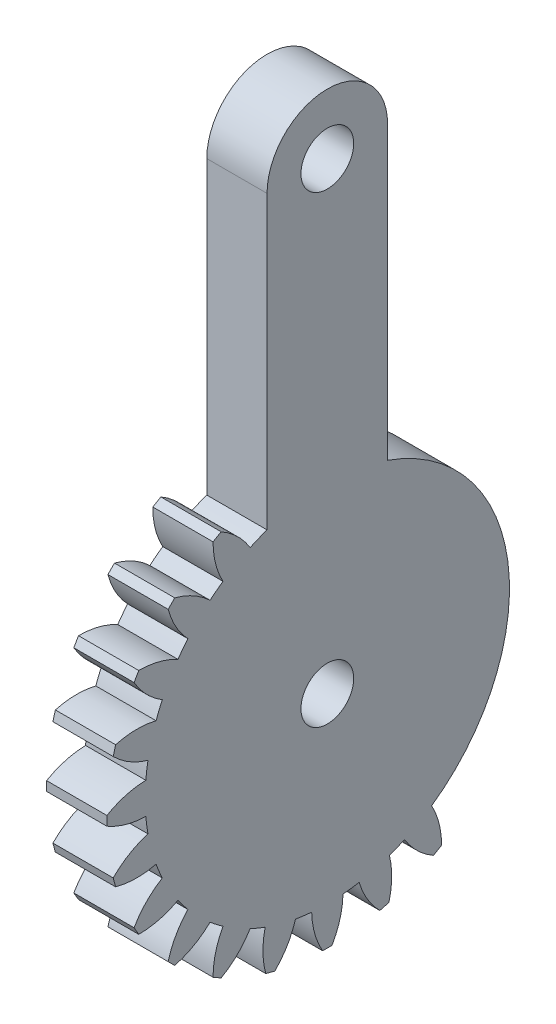
SolidWorks part; units mm, degrees
ref_plane "Front Plane" through (0, 0, 0) normal (1, 0, 0) x (0, 1, 0)
ref_plane "Top Plane" through (0, 0, 0) normal (0, 0, 1) x (0, 1, 0)
ref_plane "Right Plane" through (0, 0, 0) normal (0, 1, 0) x (-1, 0, 0)
sketch "Sketch1" plane through (0, 0, 0) normal (1, 0, 0) x (0, 1, 0)
  line L0 (0, 0) -> (30.75, 0) construction
  line L1 (0, 14.63) -> (0, -14.63) construction
  line L2 (-0.31, 14.63) -> (0.31, 14.63)
  line L3 (3.4871, 14.2117) -> (4.086, 14.0513)
  line L4 (7.0465, 12.825) -> (7.5835, 12.515)
  line L5 (10.1258, 10.5642) -> (10.5642, 10.1258)
  line L6 (12.515, 7.5835) -> (12.825, 7.0465)
  line L10 (12.825, -7.0465) -> (12.515, -7.5835)
  line L11 (10.5642, -10.1258) -> (10.1258, -10.5642)
  line L12 (7.5835, -12.515) -> (7.0465, -12.825)
  line L13 (4.086, -14.0513) -> (3.4871, -14.2117)
  line L14 (0.31, -14.63) -> (-0.31, -14.63)
  line L15 (-3.4871, -14.2117) -> (-4.086, -14.0513)
  line L16 (-7.0465, -12.825) -> (-7.5835, -12.515)
  line L17 (-10.1258, -10.5642) -> (-10.5642, -10.1258)
  line L18 (-12.515, -7.5835) -> (-12.825, -7.0465)
  line L19 (-14.0513, -4.086) -> (-14.2117, -3.4871)
  line L20 (-14.63, -0.31) -> (-14.63, 0.31)
  line L21 (-14.2117, 3.4871) -> (-14.0513, 4.086)
  line L22 (-12.825, 7.0465) -> (-12.515, 7.5835)
  line L23 (-10.5642, 10.1258) -> (-10.1258, 10.5642)
  line L24 (-7.5835, 12.515) -> (-7.0465, 12.825)
  line L25 (-4.086, 14.0513) -> (-3.4871, 14.2117)
  line L26 (30.75, 4) -> (30.75, -4) construction
  line L27 (30.75, 4) -> (11.4091, 4)
  line L28 (30.75, -4) -> (11.4091, -4)
  line L29 (14.0743, 4) -> (14.2117, 3.4871) [skipped]
  line L30 (14.63, 0) -> (14.63, -0.31) [skipped]
  line L31 (14.0743, -4) -> (14.0513, -4.086) [skipped]
  arc A0 (-6.9233, 9.9114) -> (-7.7818, 9.2526) centre (0, 0) ccw
  circle A1 centre (0, 0) radius 1.75
  circle A2 centre (30.75, 0) radius 1.75
  arc A3 (-1.04, 12.0452) -> (-0.31, 14.63) centre (4.3585, 11.9161) cw
  arc A4 (1.04, 12.0452) -> (0.31, 14.63) centre (-4.3585, 11.9161) ccw
  arc A5 (2.113, 11.9039) -> (3.4871, 14.2117) centre (7.294, 10.382) cw
  arc A6 (4.1221, 11.3656) -> (4.086, 14.0513) centre (-1.1258, 12.6381) ccw
  arc A7 (5.1219, 10.9514) -> (7.0465, 12.825) centre (9.7326, 8.1404) cw
  arc A8 (6.9233, 9.9114) -> (7.5835, 12.515) centre (2.1835, 12.4988) ccw
  arc A9 (7.7818, 9.2526) -> (10.1258, 10.5642) centre (11.5078, 5.344) cw
  arc A10 (9.2526, 7.7818) -> (10.5642, 10.1258) centre (5.344, 11.5078) ccw
  arc A11 (9.9114, 6.9233) -> (12.515, 7.5835) centre (12.4988, 2.1835) cw
  arc A12 (10.9514, 5.1219) -> (12.825, 7.0465) centre (8.1404, 9.7326) ccw
  arc A13 (11.4091, 4) -> (10.9514, 5.1219) centre (0, 0) ccw
  arc A19 (10.9514, -5.1219) -> (12.825, -7.0465) centre (8.1404, -9.7326) cw
  arc A20 (9.9114, -6.9233) -> (12.515, -7.5835) centre (12.4988, -2.1835) ccw
  arc A21 (9.2526, -7.7818) -> (10.5642, -10.1258) centre (5.344, -11.5078) cw
  arc A22 (7.7818, -9.2526) -> (10.1258, -10.5642) centre (11.5078, -5.344) ccw
  arc A23 (6.9233, -9.9114) -> (7.5835, -12.515) centre (2.1835, -12.4988) cw
  arc A24 (5.1219, -10.9514) -> (7.0465, -12.825) centre (9.7326, -8.1404) ccw
  arc A25 (4.1221, -11.3656) -> (4.086, -14.0513) centre (-1.1258, -12.6381) cw
  arc A26 (2.113, -11.9039) -> (3.4871, -14.2117) centre (7.294, -10.382) ccw
  arc A27 (1.04, -12.0452) -> (0.31, -14.63) centre (-4.3585, -11.9161) cw
  arc A28 (-1.04, -12.0452) -> (-0.31, -14.63) centre (4.3585, -11.9161) ccw
  arc A29 (-2.113, -11.9039) -> (-3.4871, -14.2117) centre (-7.294, -10.382) cw
  arc A30 (-4.1221, -11.3656) -> (-4.086, -14.0513) centre (1.1258, -12.6381) ccw
  arc A31 (-5.1219, -10.9514) -> (-7.0465, -12.825) centre (-9.7326, -8.1404) cw
  arc A32 (-6.9233, -9.9114) -> (-7.5835, -12.515) centre (-2.1835, -12.4988) ccw
  arc A33 (-7.7818, -9.2526) -> (-10.1258, -10.5642) centre (-11.5078, -5.344) cw
  arc A34 (-9.2526, -7.7818) -> (-10.5642, -10.1258) centre (-5.344, -11.5078) ccw
  arc A35 (-9.9114, -6.9233) -> (-12.515, -7.5835) centre (-12.4988, -2.1835) cw
  arc A36 (-10.9514, -5.1219) -> (-12.825, -7.0465) centre (-8.1404, -9.7326) ccw
  arc A37 (-11.3656, -4.1221) -> (-14.0513, -4.086) centre (-12.6381, 1.1258) cw
  arc A38 (-11.9039, -2.113) -> (-14.2117, -3.4871) centre (-10.382, -7.294) ccw
  arc A39 (-12.0452, -1.04) -> (-14.63, -0.31) centre (-11.9161, 4.3585) cw
  arc A40 (-12.0452, 1.04) -> (-14.63, 0.31) centre (-11.9161, -4.3585) ccw
  arc A41 (-11.9039, 2.113) -> (-14.2117, 3.4871) centre (-10.382, 7.294) cw
  arc A42 (-11.3656, 4.1221) -> (-14.0513, 4.086) centre (-12.6381, -1.1258) ccw
  arc A43 (-10.9514, 5.1219) -> (-12.825, 7.0465) centre (-8.1404, 9.7326) cw
  arc A44 (-9.9114, 6.9233) -> (-12.515, 7.5835) centre (-12.4988, 2.1835) ccw
  arc A45 (-9.2526, 7.7818) -> (-10.5642, 10.1258) centre (-5.344, 11.5078) cw
  arc A46 (-7.7818, 9.2526) -> (-10.1258, 10.5642) centre (-11.5078, 5.344) ccw
  arc A47 (-6.9233, 9.9114) -> (-7.5835, 12.515) centre (-2.1835, 12.4988) cw
  arc A48 (-5.1219, 10.9514) -> (-7.0465, 12.825) centre (-9.7326, 8.1404) ccw
  arc A49 (-4.1221, 11.3656) -> (-4.086, 14.0513) centre (1.1258, 12.6381) cw
  arc A50 (-2.113, 11.9039) -> (-3.4871, 14.2117) centre (-7.294, 10.382) ccw
  arc A51 (30.75, -4) -> (30.75, 4) centre (30.75, 0) ccw
  arc A52 (-4.1221, 11.3656) -> (-5.1219, 10.9514) centre (0, 0) ccw
  arc A53 (-9.2526, 7.7818) -> (-9.9114, 6.9233) centre (0, 0) ccw
  arc A54 (-10.9514, 5.1219) -> (-11.3656, 4.1221) centre (0, 0) ccw
  arc A55 (-11.9039, 2.113) -> (-12.0452, 1.04) centre (0, 0) ccw
  arc A56 (-12.0452, -1.04) -> (-11.9039, -2.113) centre (0, 0) ccw
  arc A57 (-11.3656, -4.1221) -> (-10.9514, -5.1219) centre (0, 0) ccw
  arc A58 (-9.9114, -6.9233) -> (11.4091, -4) centre (0, 0) ccw
  arc A59 (-1.04, 12.0452) -> (-2.113, 11.9039) centre (0, 0) ccw
  arc A60 (2.113, 11.9039) -> (1.04, 12.0452) centre (0, 0) ccw
  arc A61 (5.1219, 10.9514) -> (4.1221, 11.3656) centre (0, 0) ccw
  arc A62 (7.7818, 9.2526) -> (6.9233, 9.9114) centre (0, 0) ccw
  arc A63 (9.9114, 6.9233) -> (9.2526, 7.7818) centre (0, 0) ccw
  arc A64 (11.3656, 4.1221) -> (14.0513, 4.086) centre (12.6381, -1.1258) cw [skipped]
  arc A65 (11.9039, 2.113) -> (14.2117, 3.4871) centre (10.382, 7.294) ccw [skipped]
  arc A66 (12.0452, 1.04) -> (14.63, 0.31) centre (11.9161, -4.3585) cw [skipped]
  arc A67 (12.0452, -1.04) -> (14.63, -0.31) centre (11.9161, 4.3585) ccw [skipped]
  arc A68 (11.9039, -2.113) -> (14.2117, -3.4871) centre (10.382, -7.294) cw [skipped]
  arc A69 (11.3656, -4.1221) -> (14.0513, -4.086) centre (12.6381, 1.1258) ccw [skipped]
  point P8 (0, 0)
  dimension "D2" = 24.18
  dimension "D3" = 3.5
  dimension "D4" = 3.5
  dimension "D6" = 5.4
  dimension "D10" = 8
  dimension "D1" = 30.75
  dimension "D5" = 29.26
  dimension "D7" = 1.04
  dimension "D8" = 0.31
  dimension "D9" = 24
extrude "Boss-Extrude1" add sketch "Sketch1" along normal blind 4 contours A11 A63 A10 L5 A9 A62 A8 L4 A7 A61 A6 L3 A5 A60 A4 L2 A3 A59 A50 L25 A49 A52 A48 L24 A47 A0 A46 L23 A45 A53 A44 L22 A43 A54 A42 L21 A41 A55 A40 L20 A39 A56 A38 L19 A37 A57 A36 L18 A35 A58
sketch "Sketch2" plane through (4, 0, 0) normal (1, 0, 0) x (0, 1, 0)
  circle A0 centre (0, 0) radius 13 construction
  dimension "D1" = 26
